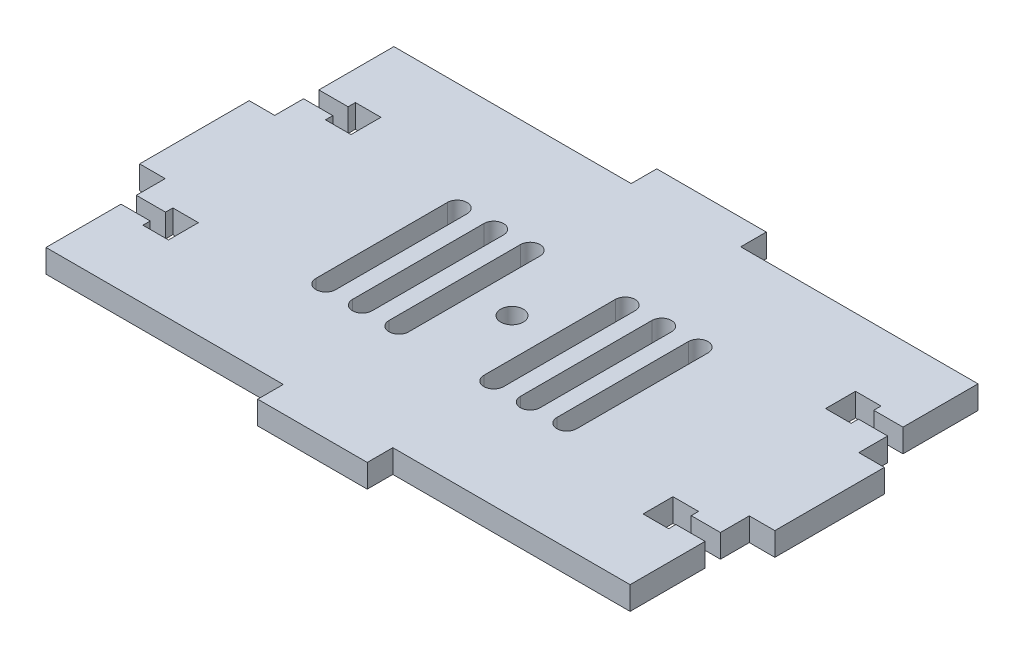
SolidWorks part; units mm, degrees
ref_plane "Front Plane" through (0, 0, 0) normal (0, 0, 1) x (1, 0, 0)
ref_plane "Top Plane" through (0, 0, 0) normal (0, 1, 0) x (1, 0, 0)
ref_plane "Right Plane" through (0, 0, 0) normal (1, 0, 0) x (0, 0, -1)
sketch "Sketch2" plane through (0, 0, 0) normal (0, 1, 0) x (1, 0, 0)
  line L0 (0, -1.7463) -> (0, 1.7463) construction
  line L1 (-40, 23.825) -> (40, 23.825)
  line L2 (-40, 23.825) -> (-40, -23.825)
  line L3 (-40, -23.825) -> (40, -23.825)
  line L4 (40, 23.825) -> (40, -23.825)
  point P4 (0, -23.825)
  dimension "D1" = 47.65
  dimension "D2" = 80
  dimension "D4" = 23.825
extrude "Boss-Extrude1" add sketch "Sketch2" along normal blind 3.175
sketch "Sketch3" plane through (0, 3.175, 0) normal (0, 1, 0) x (1, 0, 0)
  line L0 (40, 23.825) -> (-40, 23.825) construction
  line L1 (-7.5, 23.825) -> (7.5, 23.825)
  line L2 (-7.5, 23.825) -> (-7.5, 27.325)
  line L3 (-7.5, 27.325) -> (7.5, 27.325)
  line L4 (7.5, 23.825) -> (7.5, 27.325)
  point P6 (0, 23.825)
  dimension "D1" = 15
  dimension "D2" = 3.5
  dimension "D3" = 0
extrude "Boss-Extrude2" add sketch "Sketch3" against normal blind 3.175
sketch "Sketch4" plane through (0, 3.175, 0) normal (0, 1, 0) x (1, 0, 0)
  line L0 (-40, 23.825) -> (-40, -23.825) construction
  line L1 (-40, 7.5) -> (-43.5, 7.5)
  line L2 (-40, 7.5) -> (-40, -7.5)
  line L3 (-40, -7.5) -> (-43.5, -7.5)
  line L4 (-43.5, 7.5) -> (-43.5, -7.5)
  dimension "D1" = 15
  dimension "D2" = 3.5
  dimension "D3" = 7.5
extrude "Boss-Extrude3" add sketch "Sketch4" against normal blind 3.175
mirror "Mirror1" about plane through (0, 0, 0) normal (1, 0, 0) of "Boss-Extrude3"
mirror "Mirror2" about plane through (0, 0, 0) normal (0, 0, 1) of "Boss-Extrude2", "Mirror1"
sketch "Sketch5" plane through (0, 3.175, 0) normal (0, 1, 0) x (1, 0, 0)
  line L0 (-40, 13.55) -> (-36, 13.55)
  line L1 (-40, 23.825) -> (-40, 7.5) construction
  line L2 (-36, 13.55) -> (-36, 14.55)
  line L3 (-36, 14.55) -> (-32.5, 14.55)
  line L4 (-32.5, 14.55) -> (-32.5, 10.45)
  line L5 (-32.5, 10.45) -> (-36, 10.45)
  line L6 (-36, 10.45) -> (-36, 11.45)
  line L7 (-36, 11.45) -> (-40, 11.45)
  line L8 (-40, 11.45) -> (-40, 13.55)
  line L9 (-40, 7.5) -> (-43.5, 7.5) construction
  point P4 (-40, 12.5)
  dimension "D1" = 2.1
  dimension "D2" = 4.1
  dimension "D3" = 7.5
  dimension "D4" = 3.5
  dimension "D5" = 5
  dimension "D6" = 2.05
extrude "Cut-Extrude1" cut sketch "Sketch5" against normal blind 10
mirror "Mirror3" about plane through (0, 0, 0) normal (0, 0, 1) of "Cut-Extrude1"
mirror "Mirror4" about plane through (0, 0, 0) normal (1, 0, 0) of "Mirror3", "Cut-Extrude1"
sketch "Sketch6" plane through (0, 3.175, 0) normal (0, 1, 0) x (1, 0, 0)
  line L0 (5.15, -9) -> (5.15, 9)
  line L1 (7.85, 9) -> (7.85, -9)
  arc A0 (7.85, 9) -> (5.15, 9) centre (6.5, 9) ccw
  arc A1 (5.15, -9) -> (7.85, -9) centre (6.5, -9) ccw
  point P6 (7.85, 0)
  dimension "D1" = 18
  dimension "D2" = 1.35
  dimension "D3" = 0
  dimension "D4" = 6.5
extrude "Cut-Extrude2" cut sketch "Sketch6" against normal blind 10
pattern_linear "LPattern1" count 3 spacing 5 along (1, 0, 0) of "Cut-Extrude2"
mirror "Mirror5" about plane through (0, 0, 0) normal (1, 0, 0) of "LPattern1", "Cut-Extrude2"
sketch "Sketch7" plane through (0, 0, 0) normal (0, 1, 0) x (1, 0, 0)
  circle A0 centre (0, 0) radius 1.55
  dimension "D1" = 3.1
extrude "Cut-Extrude6" cut sketch "Sketch7" along normal through all both and the other way through all
